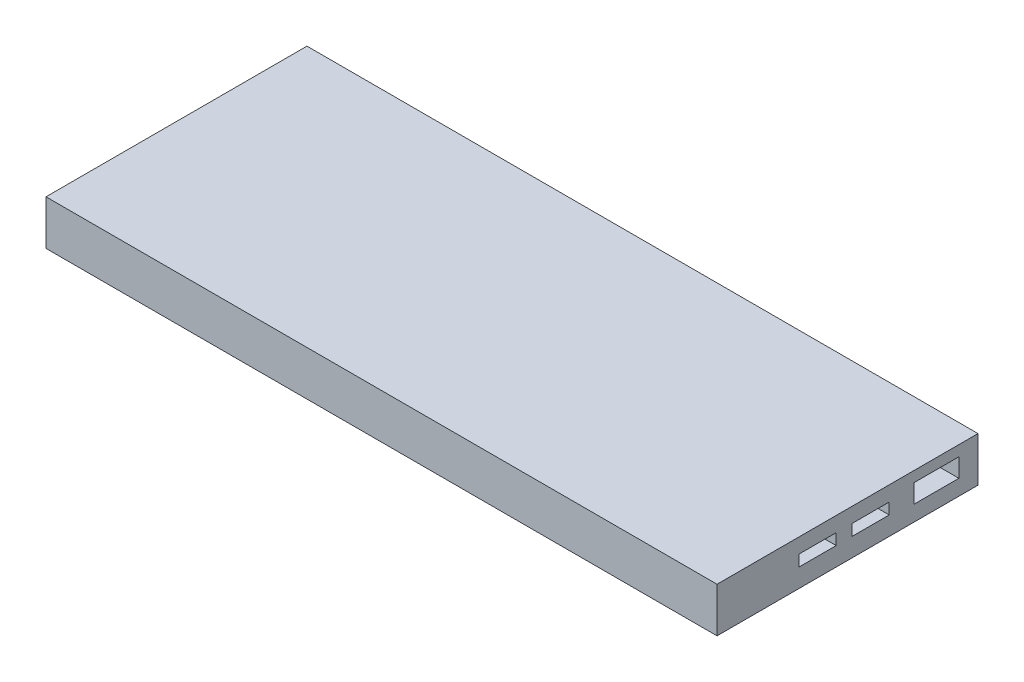
SolidWorks part; units mm, degrees
ref_plane "Front Plane" through (0, 0, 0) normal (0, 0, 1) x (1, 0, 0)
ref_plane "Top Plane" through (0, 0, 0) normal (0, 1, 0) x (1, 0, 0)
ref_plane "Right Plane" through (0, 0, 0) normal (1, 0, 0) x (0, 0, -1)
sketch "Sketch1" plane through (0, 0, 0) normal (0, 1, 0) x (1, 0, 0)
  line L1 (-90, 35) -> (90, 35)
  line L2 (-90, 35) -> (-90, -35)
  line L3 (-90, -35) -> (90, -35)
  line L4 (90, 35) -> (90, -35)
  line L5 (-90, 35) -> (90, -35) construction
  line L6 (-90, -35) -> (90, 35) construction
  point P0 (0, 0)
  dimension "D1" = 180
  dimension "D2" = 70
extrude "Boss-Extrude1" add sketch "Sketch1" along normal blind 12
sketch "Sketch2" plane through (90, 0, 0) normal (1, 0, 0) x (0, 0, -1)
  line L0 (-35, 0) -> (35, 0) construction
  line L1 (29.8749, 4.1697) -> (17.8749, 4.1697)
  line L2 (29.8749, 4.1697) -> (29.8749, 9.1697)
  line L3 (29.8749, 9.1697) -> (17.8749, 9.1697)
  line L4 (17.8749, 4.1697) -> (17.8749, 9.1697)
  line L5 (11.1869, 5) -> (1.1869, 5)
  line L6 (11.1869, 5) -> (11.1869, 8)
  line L7 (11.1869, 8) -> (1.1869, 8)
  line L8 (1.1869, 5) -> (1.1869, 8)
  line L9 (-3.0434, 5) -> (-13.0434, 5)
  line L10 (-3.0434, 5) -> (-3.0434, 8)
  line L11 (-3.0434, 8) -> (-13.0434, 8)
  line L12 (-13.0434, 5) -> (-13.0434, 8)
  dimension "D1" = 10
  dimension "D2" = 3
  dimension "D3" = 3
  dimension "D4" = 10
  dimension "D5" = 3
  dimension "D6" = 5
  dimension "D7" = 5
  dimension "D8" = 12
  dimension "D9" = 5
  dimension "D10" = 5.1251
  dimension "D11" = 23.8131
  dimension "D12" = 38.0434
  dimension "D13" = 4.1697
extrude "Cut-Extrude1" cut sketch "Sketch2" against normal blind 10
